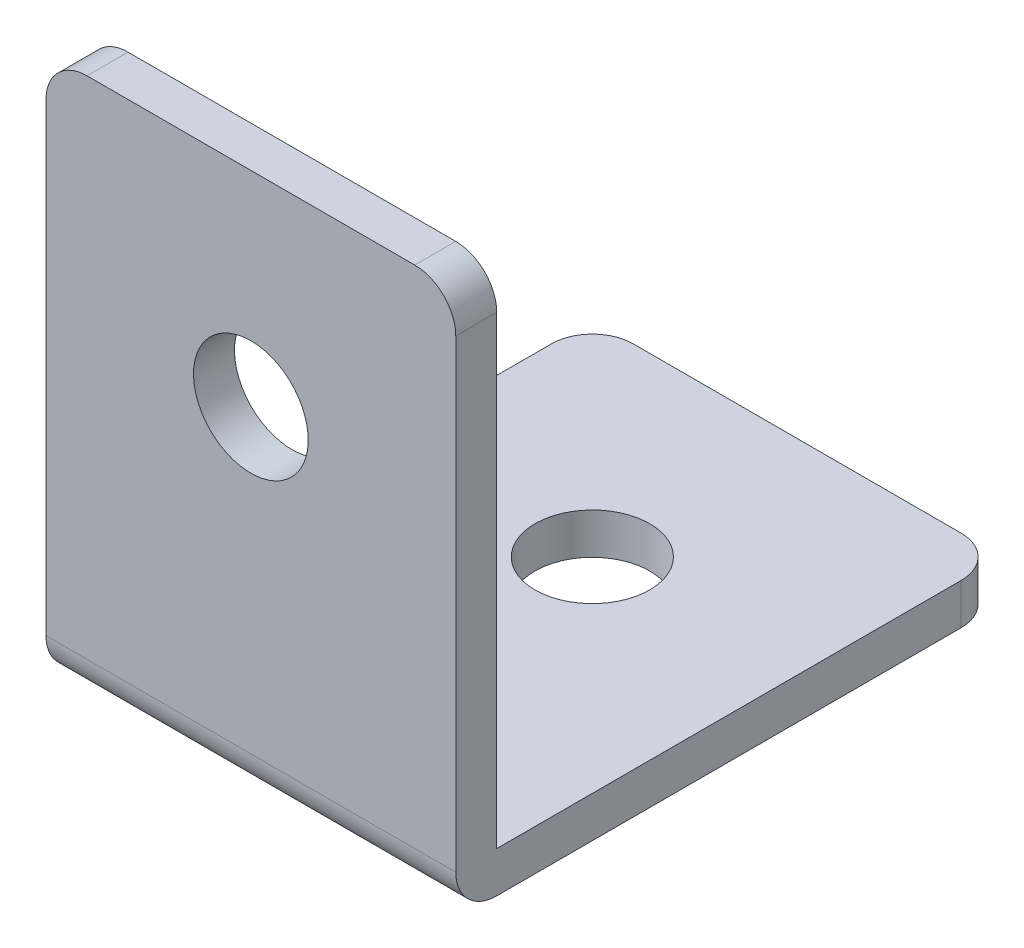
SolidWorks part; units mm, degrees
ref_plane "Front Plane" through (0, 0, 0) normal (0, 0, 1) x (1, 0, 0)
ref_plane "Top Plane" through (0, 0, 0) normal (0, 1, 0) x (1, 0, 0)
ref_plane "Right Plane" through (0, 0, 0) normal (1, 0, 0) x (0, 0, -1)
sketch "Sketch1" plane through (0, 0, 0) normal (1, 0, 0) x (0, 0, -1)
  line L0 (0, 20) -> (0, 1.5)
  line L1 (1.5, 0) -> (20, 0)
  arc A0 (0, 1.5) -> (1.5, 0) centre (1.5, 1.5) ccw
  point P6 (0, 0)
  dimension "D3" = 1.5
  dimension "D1" = 20
  dimension "D2" = 20
extrude "Extrude-Thin1" add sketch "Sketch1" along normal blind 15 thin
hole_wizard "Ø4.2 (4.2) Diameter Hole1" positions "Sketch3" profile "Sketch2" hole size "Ø4.2" standard "ANSI Metric" end condition through all
sketch "Sketch3" plane through (0, 1.5, 0) normal (0, 1, 0) x (1, 0, 0)
  line L0 (15, 12.5) -> (0, 12.5) construction
  line L1 (15, 1.5) -> (15, 20) construction
  line L2 (0, 1.5) -> (0, 20) construction
  line L5 (15, 20) -> (0, 20) construction
  point P0 (7.5, 12.5)
  dimension "D1" = 12.5
sketch "Sketch2" plane through (7.5, 1.5, -12.5) normal (1, 0, 0) x (0, 0, 1)
  line L0 (0, 0) -> (0, 1.5)
  line L1 (0, 1.5) -> (2.1, 1.5)
  line L2 (2.1, 1.5) -> (2.1, 0)
  line L5 (2.1, 0) -> (0, 0)
  line L11 (0, -6.35) -> (0, 107.95) construction
  dimension "Thru Hole Dia." = 4.2
  dimension "Thru Hole Depth" = 1.5
hole_wizard "Ø4.2 (4.2) Diameter Hole2" positions "Sketch5" profile "Sketch4" hole size "Ø4.2" standard "ANSI Metric" end condition through all
sketch "Sketch5" plane through (0, 0, -1.5) normal (0, 0, -1) x (-1, 0, 0)
  line L0 (0, 12.5) -> (-15, 12.5) construction
  line L1 (0, 20) -> (0, 1.5) construction
  line L2 (-15, 20) -> (-15, 1.5) construction
  point P0 (-7.5, 12.5)
  dimension "D1" = 12.5
sketch "Sketch4" plane through (7.5, 12.5, -1.5) normal (1, 0, 0) x (0, 1, 0)
  line L0 (0, 0) -> (0, 1.5)
  line L1 (0, 1.5) -> (2.1, 1.5)
  line L2 (2.1, 1.5) -> (2.1, 0)
  line L5 (2.1, 0) -> (0, 0)
  line L11 (0, -6.35) -> (0, 107.95) construction
  dimension "Thru Hole Dia." = 4.2
  dimension "Thru Hole Depth" = 1.5
fillet "Fillet1" radius 1.5 4 edges at (0, 0.75, -20) (15, 0.75, -20) (0, 20, -0.75) (15, 20, -0.75)
equation "\"L1\"= 20"
equation "\"L2\"= 20"
equation "\"W\"= 15"
equation "\"B\"= 1.5"
equation "\"d\"= 4.2"
equation "\"D2@Sketch1\"=\"L2\""
equation "\"D1@Sketch1\"=\"L1\""
equation "\"D5@Extrude-Thin1\"=\"B\""
equation "\"D1@Extrude-Thin1\"=\"W\""
equation "\"D3@Sketch1\"=\"B\""
equation "\"D1@Fillet1\"=\"B\""
equation "\"L3\" = 12.5"
equation "\"L4\"= 12.5"
equation "\"D1@Sketch3\"=\"L3\""
equation "\"D1@Sketch5\"=\"L4\""
